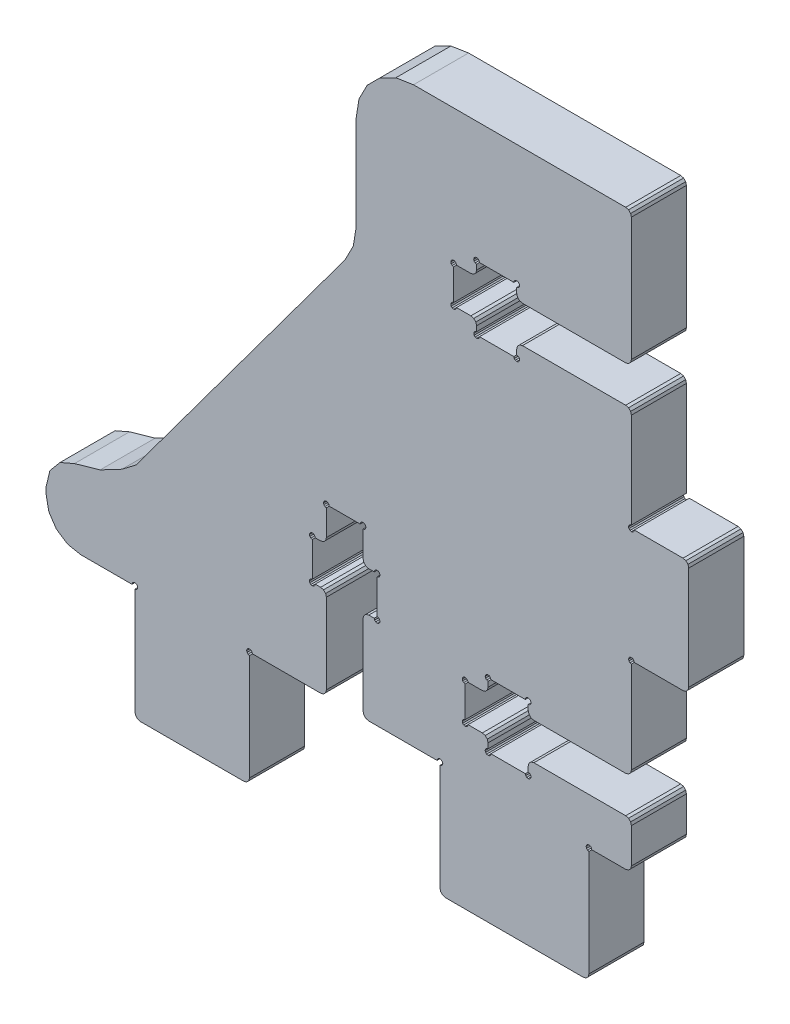
SolidWorks part; units mm, degrees
ref_plane "Plan de face" through (0, 0, 0) normal (0, 0, 1) x (1, 0, 0)
ref_plane "Plan de dessus" through (0, 0, 0) normal (0, 1, 0) x (1, 0, 0)
ref_plane "Plan de droite" through (0, 0, 0) normal (1, 0, 0) x (0, 0, -1)
ref_plane "Plan1" through (0, 0, 0) normal (0, 0, -1) x (-1, 0, 0)
sketch "Esquisse1" plane through (0, 0, 0) normal (0, 0, -1) x (-1, 0, 0)
  line L0 (-7.8359, 19.1892) -> (-26.0478, 43.7777)
  line L1 (-26.0478, 43.7777) -> (-26.778, 45.1868)
  line L2 (-26.778, 45.1868) -> (-27.0298, 46.7537)
  line L3 (-27.0298, 46.7537) -> (-27.0298, 55)
  line L4 (-27.0298, 55) -> (-27.2746, 56.5451)
  line L5 (-27.2746, 56.5451) -> (-27.9847, 57.9389)
  line L6 (-27.9847, 57.9389) -> (-29.0909, 59.0451)
  line L7 (-29.0909, 59.0451) -> (-30.4847, 59.7553)
  line L8 (-30.4847, 59.7553) -> (-32.0298, 60)
  line L9 (-32.0298, 60) -> (-50.5298, 60)
  line L10 (-50.5298, 60) -> (-50.7798, 59.933)
  line L11 (-50.7798, 59.933) -> (-50.9628, 59.75)
  line L12 (-50.9628, 59.75) -> (-51.0298, 59.5)
  line L13 (-51.0298, 59.5) -> (-51.0298, 48.75)
  line L14 (-51.0298, 48.75) -> (-50.9628, 48.5)
  line L15 (-50.9628, 48.5) -> (-50.7798, 48.317)
  line L16 (-50.7798, 48.317) -> (-50.5298, 48.25)
  line L17 (-50.5298, 48.25) -> (-41.5298, 48.25)
  line L18 (-41.5298, 48.25) -> (-41.2798, 48.317)
  line L19 (-41.2798, 48.317) -> (-41.0968, 48.5)
  line L20 (-41.0968, 48.5) -> (-41.0298, 48.75)
  line L21 (-41.0298, 48.75) -> (-41.0298, 49.2)
  line L22 (-41.0298, 49.2) -> (-41.1548, 49.2335)
  line L23 (-41.1548, 49.2335) -> (-41.2463, 49.325)
  line L24 (-41.2463, 49.325) -> (-41.2798, 49.45)
  line L25 (-41.2798, 49.45) -> (-41.2463, 49.575)
  line L26 (-41.2463, 49.575) -> (-41.1548, 49.6665)
  line L27 (-41.1548, 49.6665) -> (-41.0298, 49.7)
  line L28 (-41.0298, 49.7) -> (-40.9048, 49.6665)
  line L29 (-40.9048, 49.6665) -> (-40.8133, 49.575)
  line L30 (-40.8133, 49.575) -> (-40.7798, 49.45)
  line L31 (-40.7798, 49.45) -> (-37.7798, 49.45)
  line L32 (-37.7798, 49.45) -> (-37.7463, 49.575)
  line L33 (-37.7463, 49.575) -> (-37.6548, 49.6665)
  line L34 (-37.6548, 49.6665) -> (-37.5298, 49.7)
  line L35 (-37.5298, 49.7) -> (-37.4048, 49.6665)
  line L36 (-37.4048, 49.6665) -> (-37.3133, 49.575)
  line L37 (-37.3133, 49.575) -> (-37.2798, 49.45)
  line L38 (-37.2798, 49.45) -> (-37.3133, 49.325)
  line L39 (-37.3133, 49.325) -> (-37.4048, 49.2335)
  line L40 (-37.4048, 49.2335) -> (-37.5298, 49.2)
  line L41 (-37.5298, 49.2) -> (-37.5298, 48.75)
  line L42 (-37.5298, 48.75) -> (-37.4628, 48.5)
  line L43 (-37.4628, 48.5) -> (-37.2798, 48.317)
  line L44 (-37.2798, 48.317) -> (-37.0298, 48.25)
  line L45 (-37.0298, 48.25) -> (-35.7798, 48.25)
  line L46 (-35.7798, 48.25) -> (-35.7463, 48.375)
  line L47 (-35.7463, 48.375) -> (-35.6548, 48.4665)
  line L48 (-35.6548, 48.4665) -> (-35.5298, 48.5)
  line L49 (-35.5298, 48.5) -> (-35.4048, 48.4665)
  line L50 (-35.4048, 48.4665) -> (-35.3133, 48.375)
  line L51 (-35.3133, 48.375) -> (-35.2798, 48.25)
  line L52 (-35.2798, 48.25) -> (-35.3133, 48.125)
  line L53 (-35.3133, 48.125) -> (-35.4048, 48.0335)
  line L54 (-35.4048, 48.0335) -> (-35.5298, 48)
  line L55 (-35.5298, 48) -> (-35.5298, 45.3)
  line L56 (-35.5298, 45.3) -> (-35.4048, 45.2665)
  line L57 (-35.4048, 45.2665) -> (-35.3133, 45.175)
  line L58 (-35.3133, 45.175) -> (-35.2798, 45.05)
  line L59 (-35.2798, 45.05) -> (-35.3133, 44.925)
  line L60 (-35.3133, 44.925) -> (-35.4048, 44.8335)
  line L61 (-35.4048, 44.8335) -> (-35.5298, 44.8)
  line L62 (-35.5298, 44.8) -> (-35.6548, 44.8335)
  line L63 (-35.6548, 44.8335) -> (-35.7463, 44.925)
  line L64 (-35.7463, 44.925) -> (-35.7798, 45.05)
  line L65 (-35.7798, 45.05) -> (-37.0298, 45.05)
  line L66 (-37.0298, 45.05) -> (-37.2798, 44.983)
  line L67 (-37.2798, 44.983) -> (-37.4628, 44.8)
  line L68 (-37.4628, 44.8) -> (-37.5298, 44.55)
  line L69 (-37.5298, 44.55) -> (-37.5298, 44.1)
  line L70 (-37.5298, 44.1) -> (-37.4048, 44.0665)
  line L71 (-37.4048, 44.0665) -> (-37.3133, 43.975)
  line L72 (-37.3133, 43.975) -> (-37.2798, 43.85)
  line L73 (-37.2798, 43.85) -> (-37.3133, 43.725)
  line L74 (-37.3133, 43.725) -> (-37.4048, 43.6335)
  line L75 (-37.4048, 43.6335) -> (-37.5298, 43.6)
  line L76 (-37.5298, 43.6) -> (-37.6548, 43.6335)
  line L77 (-37.6548, 43.6335) -> (-37.7463, 43.725)
  line L78 (-37.7463, 43.725) -> (-37.7798, 43.85)
  line L79 (-37.7798, 43.85) -> (-40.7798, 43.85)
  line L80 (-40.7798, 43.85) -> (-40.8133, 43.725)
  line L81 (-40.8133, 43.725) -> (-40.9048, 43.6335)
  line L82 (-40.9048, 43.6335) -> (-41.0298, 43.6)
  line L83 (-41.0298, 43.6) -> (-41.1548, 43.6335)
  line L84 (-41.1548, 43.6335) -> (-41.2463, 43.725)
  line L85 (-41.2463, 43.725) -> (-41.2798, 43.85)
  line L86 (-41.2798, 43.85) -> (-41.2463, 43.975)
  line L87 (-41.2463, 43.975) -> (-41.1548, 44.0665)
  line L88 (-41.1548, 44.0665) -> (-41.0298, 44.1)
  line L89 (-41.0298, 44.1) -> (-41.0298, 44.55)
  line L90 (-41.0298, 44.55) -> (-41.0968, 44.8)
  line L91 (-41.0968, 44.8) -> (-41.2798, 44.983)
  line L92 (-41.2798, 44.983) -> (-41.5298, 45.05)
  line L93 (-41.5298, 45.05) -> (-50.5298, 45.05)
  line L94 (-50.5298, 45.05) -> (-50.7798, 44.983)
  line L95 (-50.7798, 44.983) -> (-50.9628, 44.8)
  line L96 (-50.9628, 44.8) -> (-51.0298, 44.55)
  line L97 (-51.0298, 44.55) -> (-51.0298, 36.25)
  line L98 (-51.0298, 36.25) -> (-50.9048, 36.2165)
  line L99 (-50.9048, 36.2165) -> (-50.8133, 36.125)
  line L100 (-50.8133, 36.125) -> (-50.7798, 36)
  line L101 (-50.7798, 36) -> (-50.8133, 35.875)
  line L102 (-50.8133, 35.875) -> (-50.9048, 35.7835)
  line L103 (-50.9048, 35.7835) -> (-51.0298, 35.75)
  line L104 (-51.0298, 35.75) -> (-51.1548, 35.7835)
  line L105 (-51.1548, 35.7835) -> (-51.2463, 35.875)
  line L106 (-51.2463, 35.875) -> (-51.2798, 36)
  line L107 (-51.2798, 36) -> (-55.5298, 36)
  line L108 (-55.5298, 36) -> (-55.7798, 35.933)
  line L109 (-55.7798, 35.933) -> (-55.9628, 35.75)
  line L110 (-55.9628, 35.75) -> (-56.0298, 35.5)
  line L111 (-56.0298, 35.5) -> (-56.0298, 26.5)
  line L112 (-56.0298, 26.5) -> (-55.9628, 26.25)
  line L113 (-55.9628, 26.25) -> (-55.7798, 26.067)
  line L114 (-55.7798, 26.067) -> (-55.5298, 26)
  line L115 (-55.5298, 26) -> (-51.2798, 26)
  line L116 (-51.2798, 26) -> (-51.2463, 26.125)
  line L117 (-51.2463, 26.125) -> (-51.1548, 26.2165)
  line L118 (-51.1548, 26.2165) -> (-51.0298, 26.25)
  line L119 (-51.0298, 26.25) -> (-50.9048, 26.2165)
  line L120 (-50.9048, 26.2165) -> (-50.8133, 26.125)
  line L121 (-50.8133, 26.125) -> (-50.7798, 26)
  line L122 (-50.7798, 26) -> (-50.8133, 25.875)
  line L123 (-50.8133, 25.875) -> (-50.9048, 25.7835)
  line L124 (-50.9048, 25.7835) -> (-51.0298, 25.75)
  line L125 (-51.0298, 25.75) -> (-51.0298, 17.75)
  line L126 (-51.0298, 17.75) -> (-50.9628, 17.5)
  line L127 (-50.9628, 17.5) -> (-50.7798, 17.317)
  line L128 (-50.7798, 17.317) -> (-50.5298, 17.25)
  line L129 (-50.5298, 17.25) -> (-42.5298, 17.25)
  line L130 (-42.5298, 17.25) -> (-42.2798, 17.317)
  line L131 (-42.2798, 17.317) -> (-42.0968, 17.5)
  line L132 (-42.0968, 17.5) -> (-42.0298, 17.75)
  line L133 (-42.0298, 17.75) -> (-42.0298, 18.2)
  line L134 (-42.0298, 18.2) -> (-42.1548, 18.2335)
  line L135 (-42.1548, 18.2335) -> (-42.2463, 18.325)
  line L136 (-42.2463, 18.325) -> (-42.2798, 18.45)
  line L137 (-42.2798, 18.45) -> (-42.2463, 18.575)
  line L138 (-42.2463, 18.575) -> (-42.1548, 18.6665)
  line L139 (-42.1548, 18.6665) -> (-42.0298, 18.7)
  line L140 (-42.0298, 18.7) -> (-41.9048, 18.6665)
  line L141 (-41.9048, 18.6665) -> (-41.8133, 18.575)
  line L142 (-41.8133, 18.575) -> (-41.7798, 18.45)
  line L143 (-41.7798, 18.45) -> (-38.7798, 18.45)
  line L144 (-38.7798, 18.45) -> (-38.7463, 18.575)
  line L145 (-38.7463, 18.575) -> (-38.6548, 18.6665)
  line L146 (-38.6548, 18.6665) -> (-38.5298, 18.7)
  line L147 (-38.5298, 18.7) -> (-38.4048, 18.6665)
  line L148 (-38.4048, 18.6665) -> (-38.3133, 18.575)
  line L149 (-38.3133, 18.575) -> (-38.2798, 18.45)
  line L150 (-38.2798, 18.45) -> (-38.3133, 18.325)
  line L151 (-38.3133, 18.325) -> (-38.4048, 18.2335)
  line L152 (-38.4048, 18.2335) -> (-38.5298, 18.2)
  line L153 (-38.5298, 18.2) -> (-38.5298, 17.75)
  line L154 (-38.5298, 17.75) -> (-38.4629, 17.5)
  line L155 (-38.4629, 17.5) -> (-38.2798, 17.317)
  line L156 (-38.2798, 17.317) -> (-38.0298, 17.25)
  line L157 (-38.0298, 17.25) -> (-36.7798, 17.25)
  line L158 (-36.7798, 17.25) -> (-36.7463, 17.375)
  line L159 (-36.7463, 17.375) -> (-36.6548, 17.4665)
  line L160 (-36.6548, 17.4665) -> (-36.5298, 17.5)
  line L161 (-36.5298, 17.5) -> (-36.4048, 17.4665)
  line L162 (-36.4048, 17.4665) -> (-36.3133, 17.375)
  line L163 (-36.3133, 17.375) -> (-36.2798, 17.25)
  line L164 (-36.2798, 17.25) -> (-36.3133, 17.125)
  line L165 (-36.3133, 17.125) -> (-36.4048, 17.0335)
  line L166 (-36.4048, 17.0335) -> (-36.5298, 17)
  line L167 (-36.5298, 17) -> (-36.5298, 14.3)
  line L168 (-36.5298, 14.3) -> (-36.4048, 14.2665)
  line L169 (-36.4048, 14.2665) -> (-36.3133, 14.175)
  line L170 (-36.3133, 14.175) -> (-36.2798, 14.05)
  line L171 (-36.2798, 14.05) -> (-36.3133, 13.925)
  line L172 (-36.3133, 13.925) -> (-36.4048, 13.8335)
  line L173 (-36.4048, 13.8335) -> (-36.5298, 13.8)
  line L174 (-36.5298, 13.8) -> (-36.6548, 13.8335)
  line L175 (-36.6548, 13.8335) -> (-36.7463, 13.925)
  line L176 (-36.7463, 13.925) -> (-36.7798, 14.05)
  line L177 (-36.7798, 14.05) -> (-38.0298, 14.05)
  line L178 (-38.0298, 14.05) -> (-38.2798, 13.983)
  line L179 (-38.2798, 13.983) -> (-38.4629, 13.8)
  line L180 (-38.4629, 13.8) -> (-38.5298, 13.55)
  line L181 (-38.5298, 13.55) -> (-38.5298, 13.1)
  line L182 (-38.5298, 13.1) -> (-38.4048, 13.0665)
  line L183 (-38.4048, 13.0665) -> (-38.3133, 12.975)
  line L184 (-38.3133, 12.975) -> (-38.2798, 12.85)
  line L185 (-38.2798, 12.85) -> (-38.3133, 12.725)
  line L186 (-38.3133, 12.725) -> (-38.4048, 12.6335)
  line L187 (-38.4048, 12.6335) -> (-38.5298, 12.6)
  line L188 (-38.5298, 12.6) -> (-38.6548, 12.6335)
  line L189 (-38.6548, 12.6335) -> (-38.7463, 12.725)
  line L190 (-38.7463, 12.725) -> (-38.7798, 12.85)
  line L191 (-38.7798, 12.85) -> (-41.7798, 12.85)
  line L192 (-41.7798, 12.85) -> (-41.8133, 12.725)
  line L193 (-41.8133, 12.725) -> (-41.9048, 12.6335)
  line L194 (-41.9048, 12.6335) -> (-42.0298, 12.6)
  line L195 (-42.0298, 12.6) -> (-42.1548, 12.6335)
  line L196 (-42.1548, 12.6335) -> (-42.2463, 12.725)
  line L197 (-42.2463, 12.725) -> (-42.2798, 12.85)
  line L198 (-42.2798, 12.85) -> (-42.2463, 12.975)
  line L199 (-42.2463, 12.975) -> (-42.1548, 13.0665)
  line L200 (-42.1548, 13.0665) -> (-42.0298, 13.1)
  line L201 (-42.0298, 13.1) -> (-42.0298, 13.55)
  line L202 (-42.0298, 13.55) -> (-42.0968, 13.8)
  line L203 (-42.0968, 13.8) -> (-42.2798, 13.983)
  line L204 (-42.2798, 13.983) -> (-42.5298, 14.05)
  line L205 (-42.5298, 14.05) -> (-50.5298, 14.05)
  line L206 (-50.5298, 14.05) -> (-50.7798, 13.983)
  line L207 (-50.7798, 13.983) -> (-50.9628, 13.8)
  line L208 (-50.9628, 13.8) -> (-51.0298, 13.55)
  line L209 (-51.0298, 13.55) -> (-51.0298, 10.5)
  line L210 (-51.0298, 10.5) -> (-50.9628, 10.25)
  line L211 (-50.9628, 10.25) -> (-50.7798, 10.067)
  line L212 (-50.7798, 10.067) -> (-50.5298, 10)
  line L213 (-50.5298, 10) -> (-47.5798, 10)
  line L214 (-47.5798, 10) -> (-47.5463, 10.125)
  line L215 (-47.5463, 10.125) -> (-47.4548, 10.2165)
  line L216 (-47.4548, 10.2165) -> (-47.3298, 10.25)
  line L217 (-47.3298, 10.25) -> (-47.2048, 10.2165)
  line L218 (-47.2048, 10.2165) -> (-47.1133, 10.125)
  line L219 (-47.1133, 10.125) -> (-47.0798, 10)
  line L220 (-47.0798, 10) -> (-47.1133, 9.875)
  line L221 (-47.1133, 9.875) -> (-47.2048, 9.7835)
  line L222 (-47.2048, 9.7835) -> (-47.3298, 9.75)
  line L223 (-47.3298, 9.75) -> (-47.3298, 0.5)
  line L224 (-47.3298, 0.5) -> (-47.2629, 0.25)
  line L225 (-47.2629, 0.25) -> (-47.0798, 0.067)
  line L226 (-47.0798, 0.067) -> (-46.8298, 0)
  line L227 (-46.8298, 0) -> (-34.8298, 0)
  line L228 (-34.8298, 0) -> (-34.5798, 0.067)
  line L229 (-34.5798, 0.067) -> (-34.3968, 0.25)
  line L230 (-34.3968, 0.25) -> (-34.3298, 0.5)
  line L231 (-34.3298, 0.5) -> (-34.3298, 9.75)
  line L232 (-34.3298, 9.75) -> (-34.4548, 9.7835)
  line L233 (-34.4548, 9.7835) -> (-34.5463, 9.875)
  line L234 (-34.5463, 9.875) -> (-34.5798, 10)
  line L235 (-34.5798, 10) -> (-34.5463, 10.125)
  line L236 (-34.5463, 10.125) -> (-34.4548, 10.2165)
  line L237 (-34.4548, 10.2165) -> (-34.3298, 10.25)
  line L238 (-34.3298, 10.25) -> (-34.2048, 10.2165)
  line L239 (-34.2048, 10.2165) -> (-34.1133, 10.125)
  line L240 (-34.1133, 10.125) -> (-34.0798, 10)
  line L241 (-34.0798, 10) -> (-28.1298, 10)
  line L242 (-28.1298, 10) -> (-27.8798, 10.067)
  line L243 (-27.8798, 10.067) -> (-27.6968, 10.25)
  line L244 (-27.6968, 10.25) -> (-27.6298, 10.5)
  line L245 (-27.6298, 10.5) -> (-27.6298, 17.5)
  line L246 (-27.6298, 17.5) -> (-27.6968, 17.75)
  line L247 (-27.6968, 17.75) -> (-27.8798, 17.933)
  line L248 (-27.8798, 17.933) -> (-28.1298, 18)
  line L249 (-28.1298, 18) -> (-28.6048, 18)
  line L250 (-28.6048, 18) -> (-28.6383, 17.875)
  line L251 (-28.6383, 17.875) -> (-28.7298, 17.7835)
  line L252 (-28.7298, 17.7835) -> (-28.8548, 17.75)
  line L253 (-28.8548, 17.75) -> (-28.9798, 17.7835)
  line L254 (-28.9798, 17.7835) -> (-29.0713, 17.875)
  line L255 (-29.0713, 17.875) -> (-29.1048, 18)
  line L256 (-29.1048, 18) -> (-29.0713, 18.125)
  line L257 (-29.0713, 18.125) -> (-28.9798, 18.2165)
  line L258 (-28.9798, 18.2165) -> (-28.8548, 18.25)
  line L259 (-28.8548, 18.25) -> (-28.8548, 21.25)
  line L260 (-28.8548, 21.25) -> (-28.9798, 21.2835)
  line L261 (-28.9798, 21.2835) -> (-29.0713, 21.375)
  line L262 (-29.0713, 21.375) -> (-29.1048, 21.5)
  line L263 (-29.1048, 21.5) -> (-29.0713, 21.625)
  line L264 (-29.0713, 21.625) -> (-28.9798, 21.7165)
  line L265 (-28.9798, 21.7165) -> (-28.8548, 21.75)
  line L266 (-28.8548, 21.75) -> (-28.7298, 21.7165)
  line L267 (-28.7298, 21.7165) -> (-28.6383, 21.625)
  line L268 (-28.6383, 21.625) -> (-28.6048, 21.5)
  line L269 (-28.6048, 21.5) -> (-28.1298, 21.5)
  line L270 (-28.1298, 21.5) -> (-27.8798, 21.567)
  line L271 (-27.8798, 21.567) -> (-27.6968, 21.75)
  line L272 (-27.6968, 21.75) -> (-27.6298, 22)
  line L273 (-27.6298, 22) -> (-27.6298, 24.25)
  line L274 (-27.6298, 24.25) -> (-27.7548, 24.2835)
  line L275 (-27.7548, 24.2835) -> (-27.8463, 24.375)
  line L276 (-27.8463, 24.375) -> (-27.8798, 24.5)
  line L277 (-27.8798, 24.5) -> (-27.8463, 24.625)
  line L278 (-27.8463, 24.625) -> (-27.7548, 24.7165)
  line L279 (-27.7548, 24.7165) -> (-27.6298, 24.75)
  line L280 (-27.6298, 24.75) -> (-27.5048, 24.7165)
  line L281 (-27.5048, 24.7165) -> (-27.4133, 24.625)
  line L282 (-27.4133, 24.625) -> (-27.3798, 24.5)
  line L283 (-27.3798, 24.5) -> (-24.6798, 24.5)
  line L284 (-24.6798, 24.5) -> (-24.6463, 24.625)
  line L285 (-24.6463, 24.625) -> (-24.5548, 24.7165)
  line L286 (-24.5548, 24.7165) -> (-24.4298, 24.75)
  line L287 (-24.4298, 24.75) -> (-24.3048, 24.7165)
  line L288 (-24.3048, 24.7165) -> (-24.2133, 24.625)
  line L289 (-24.2133, 24.625) -> (-24.1798, 24.5)
  line L290 (-24.1798, 24.5) -> (-24.2133, 24.375)
  line L291 (-24.2133, 24.375) -> (-24.3048, 24.2835)
  line L292 (-24.3048, 24.2835) -> (-24.4298, 24.25)
  line L293 (-24.4298, 24.25) -> (-24.4298, 22)
  line L294 (-24.4298, 22) -> (-24.3628, 21.75)
  line L295 (-24.3628, 21.75) -> (-24.1798, 21.567)
  line L296 (-24.1798, 21.567) -> (-23.9298, 21.5)
  line L297 (-23.9298, 21.5) -> (-23.4548, 21.5)
  line L298 (-23.4548, 21.5) -> (-23.4213, 21.625)
  line L299 (-23.4213, 21.625) -> (-23.3298, 21.7165)
  line L300 (-23.3298, 21.7165) -> (-23.2048, 21.75)
  line L301 (-23.2048, 21.75) -> (-23.0798, 21.7165)
  line L302 (-23.0798, 21.7165) -> (-22.9883, 21.625)
  line L303 (-22.9883, 21.625) -> (-22.9548, 21.5)
  line L304 (-22.9548, 21.5) -> (-22.9883, 21.375)
  line L305 (-22.9883, 21.375) -> (-23.0798, 21.2835)
  line L306 (-23.0798, 21.2835) -> (-23.2048, 21.25)
  line L307 (-23.2048, 21.25) -> (-23.2048, 18.25)
  line L308 (-23.2048, 18.25) -> (-23.0798, 18.2165)
  line L309 (-23.0798, 18.2165) -> (-22.9883, 18.125)
  line L310 (-22.9883, 18.125) -> (-22.9548, 18)
  line L311 (-22.9548, 18) -> (-22.9883, 17.875)
  line L312 (-22.9883, 17.875) -> (-23.0798, 17.7835)
  line L313 (-23.0798, 17.7835) -> (-23.2048, 17.75)
  line L314 (-23.2048, 17.75) -> (-23.3298, 17.7835)
  line L315 (-23.3298, 17.7835) -> (-23.4213, 17.875)
  line L316 (-23.4213, 17.875) -> (-23.4548, 18)
  line L317 (-23.4548, 18) -> (-23.9298, 18)
  line L318 (-23.9298, 18) -> (-24.1798, 17.933)
  line L319 (-24.1798, 17.933) -> (-24.3628, 17.75)
  line L320 (-24.3628, 17.75) -> (-24.4298, 17.5)
  line L321 (-24.4298, 17.5) -> (-24.4298, 10.5)
  line L322 (-24.4298, 10.5) -> (-24.3628, 10.25)
  line L323 (-24.3628, 10.25) -> (-24.1798, 10.067)
  line L324 (-24.1798, 10.067) -> (-23.9298, 10)
  line L325 (-23.9298, 10) -> (-17.9798, 10)
  line L326 (-17.9798, 10) -> (-17.9463, 10.125)
  line L327 (-17.9463, 10.125) -> (-17.8548, 10.2165)
  line L328 (-17.8548, 10.2165) -> (-17.7298, 10.25)
  line L329 (-17.7298, 10.25) -> (-17.6048, 10.2165)
  line L330 (-17.6048, 10.2165) -> (-17.5133, 10.125)
  line L331 (-17.5133, 10.125) -> (-17.4798, 10)
  line L332 (-17.4798, 10) -> (-17.5133, 9.875)
  line L333 (-17.5133, 9.875) -> (-17.6048, 9.7835)
  line L334 (-17.6048, 9.7835) -> (-17.7298, 9.75)
  line L335 (-17.7298, 9.75) -> (-17.7298, 0.5)
  line L336 (-17.7298, 0.5) -> (-17.6629, 0.25)
  line L337 (-17.6629, 0.25) -> (-17.4798, 0.067)
  line L338 (-17.4798, 0.067) -> (-17.2298, 0)
  line L339 (-17.2298, 0) -> (-8.2298, 0)
  line L340 (-8.2298, 0) -> (-7.9798, 0.067)
  line L341 (-7.9798, 0.067) -> (-7.7968, 0.25)
  line L342 (-7.7968, 0.25) -> (-7.7298, 0.5)
  line L343 (-7.7298, 0.5) -> (-7.7298, 9.75)
  line L344 (-7.7298, 9.75) -> (-7.8548, 9.7835)
  line L345 (-7.8548, 9.7835) -> (-7.9463, 9.875)
  line L346 (-7.9463, 9.875) -> (-7.9798, 10)
  line L347 (-7.9798, 10) -> (-7.9463, 10.125)
  line L348 (-7.9463, 10.125) -> (-7.8548, 10.2165)
  line L349 (-7.8548, 10.2165) -> (-7.7298, 10.25)
  line L350 (-7.7298, 10.25) -> (-7.6048, 10.2165)
  line L351 (-7.6048, 10.2165) -> (-7.5133, 10.125)
  line L352 (-7.5133, 10.125) -> (-7.4798, 10)
  line L353 (-7.4798, 10) -> (-3, 10)
  line L354 (-3, 10) -> (-1.8519, 10.2284)
  line L355 (-1.8519, 10.2284) -> (-0.8787, 10.8787)
  line L356 (-0.8787, 10.8787) -> (-0.2284, 11.852)
  line L357 (-0.2284, 11.852) -> (0, 13)
  line L358 (0, 13) -> (0, 13.6579)
  line L359 (0, 13.6579) -> (-0.3173, 15.0006)
  line L360 (-0.3173, 15.0006) -> (-1.202, 16.0594)
  line L361 (-1.202, 16.0594) -> (-2.4671, 16.6101)
  line L362 (-2.4671, 16.6101) -> (-4.7019, 17.2509)
  line L363 (-4.7019, 17.2509) -> (-6.6059, 18.2541)
  line L364 (-6.6059, 18.2541) -> (-7.8359, 19.1892)
extrude "Boss.-Extru.1" add sketch "Esquisse1" against normal blind 4.8
